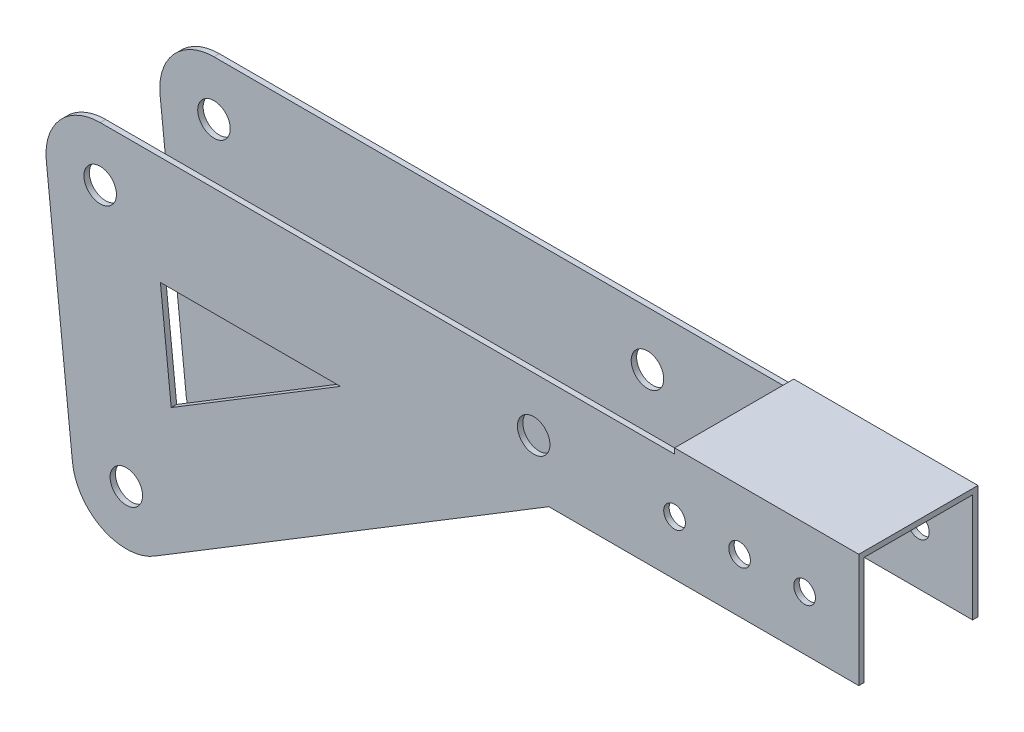
SolidWorks part; units mm, degrees
ref_plane "前视" through (0, 0, 0) normal (0, 0, 1) x (1, 0, 0)
ref_plane "上视" through (0, 0, 0) normal (0, 1, 0) x (1, 0, 0)
ref_plane "右视" through (0, 0, 0) normal (1, 0, 0) x (0, 0, -1)
sketch "草图1" plane through (0, 0, 0) normal (0, 0, 1) x (1, 0, 0)
  line L0 (-22.7233, 3.4621) -> (73.9869, 3.4621) construction
  line L1 (-6.5935, 20.8571) -> (-6.5935, -9.1197) construction
  line L2 (-6.5935, 8.4621) -> (63.4065, 8.4621)
  line L3 (-1.0384, -1.5379) -> (15.5717, -1.5379)
  line L4 (-11.5659, 2.9376) -> (-9.1534, -19.9355)
  line L5 (-1.5818, -23.6824) -> (34.8083, -1.5379)
  line L6 (-0.0366, -11.0361) -> (15.5717, -1.5379)
  line L7 (-1.0384, -1.5379) -> (-0.0366, -11.0361)
  line L8 (63.4065, 8.4621) -> (63.4065, -1.5379)
  line L9 (58.4065, 27.4351) -> (58.4065, -14.6669) construction
  line L10 (52.4065, -14.6579) -> (52.4065, 27.4351) construction
  line L11 (46.4065, 27.4351) -> (46.4065, -14.6579) construction
  line L12 (34.8083, -1.5379) -> (63.4065, -1.5379)
  circle A0 centre (-6.5935, 3.4621) radius 1.5
  circle A1 centre (33.4065, 3.4621) radius 1.5
  circle A2 centre (-4.181, -19.4111) radius 1.5
  arc A3 (-6.5935, 8.4621) -> (-11.5659, 2.9376) centre (-6.5935, 3.4621) ccw
  arc A4 (-9.1534, -19.9355) -> (-1.5818, -23.6824) centre (-4.181, -19.4111) ccw
  circle A5 centre (33.4065, 3.4621) radius 5 construction
  circle A6 centre (58.4065, 3.4621) radius 1
  circle A7 centre (52.4065, 3.4621) radius 1
  circle A8 centre (46.4065, 3.4621) radius 1
  dimension "D1" = 3
  dimension "D2" = 3
  dimension "D3" = 3
  dimension "D7" = 10
  dimension "D8" = 10
  dimension "D9" = 10
  dimension "D14" = 2
  dimension "D15" = 2
  dimension "D16" = 2
  dimension "D4" = 23
  dimension "D5" = 40
  dimension "D6" = 44
  dimension "D10" = 70
  dimension "D11" = 5
  dimension "D12" = 11
  dimension "D13" = 17
extrude "凸台-拉伸1" add sketch "草图1" along normal blind 0.5
ref_plane "基准面1" through (0, 0, -10) normal (0, 0, 1) x (1, 0, 0)
sketch "草图2" plane through (0, 0, -10) normal (0, 0, 1) x (1, 0, 0)
  line L3 (-0.0366, -11.0361) -> (15.5717, -1.5379)
  line L4 (-1.0384, -1.5379) -> (-0.0366, -11.0361)
  line L5 (15.5717, -1.5379) -> (-1.0384, -1.5379)
  line L6 (-0.0366, -11.0361) -> (15.5717, -1.5379)
  line L7 (-1.0384, -1.5379) -> (-0.0366, -11.0361)
  line L8 (15.5717, -1.5379) -> (-1.0384, -1.5379)
  line L11 (-1.5818, -23.6824) -> (34.8083, -1.5379)
  line L12 (-11.5659, 2.9376) -> (-9.1534, -19.9355)
  line L13 (63.4065, 8.4621) -> (-6.5935, 8.4621)
  line L14 (63.4065, -1.5379) -> (63.4065, 8.4621)
  line L15 (34.8083, -1.5379) -> (63.4065, -1.5379)
  line L16 (-1.5818, -23.6824) -> (34.8083, -1.5379)
  line L17 (-11.5659, 2.9376) -> (-9.1534, -19.9355)
  line L18 (63.4065, 8.4621) -> (-6.5935, 8.4621)
  line L19 (63.4065, -1.5379) -> (63.4065, 8.4621)
  line L20 (34.8083, -1.5379) -> (63.4065, -1.5379)
  circle A1 centre (-4.181, -19.4111) radius 1.5
  circle A2 centre (-4.181, -19.4111) radius 1.5
  circle A3 centre (33.4065, 3.4621) radius 1.5
  circle A4 centre (33.4065, 3.4621) radius 1.5
  circle A5 centre (-6.5935, 3.4621) radius 1.5
  circle A6 centre (-6.5935, 3.4621) radius 1.5
  circle A7 centre (52.4065, 3.4621) radius 1
  circle A8 centre (52.4065, 3.4621) radius 1
  circle A9 centre (58.4065, 3.4621) radius 1
  circle A10 centre (58.4065, 3.4621) radius 1
  circle A11 centre (46.4065, 3.4621) radius 1
  circle A12 centre (46.4065, 3.4621) radius 1
  arc A14 (-9.1534, -19.9355) -> (-1.5818, -23.6824) centre (-4.181, -19.4111) ccw
  arc A15 (-6.5935, 8.4621) -> (-11.5659, 2.9376) centre (-6.5935, 3.4621) ccw
  arc A16 (-9.1534, -19.9355) -> (-1.5818, -23.6824) centre (-4.181, -19.4111) ccw
  arc A17 (-6.5935, 8.4621) -> (-11.5659, 2.9376) centre (-6.5935, 3.4621) ccw
  dimension "D1" = 0
  dimension "D2" = 0
  dimension "D3" = 0
  dimension "D4" = 0
  dimension "D5" = 0
  dimension "D6" = 0
  dimension "D7" = 0
  dimension "D8" = 0
extrude "凸台-拉伸2" add sketch "草图2" against normal blind 0.5 separate body
ref_plane "基准面2" through (0, 8.4621, 0) normal (0, 1, 0) x (1, 0, 0)
sketch "草图3" plane through (0, 8.4621, 0) normal (0, 1, 0) x (1, 0, 0)
  line L0 (63.4065, 10.5) -> (63.4065, -0.5)
  line L1 (63.4065, -0.5) -> (46.4065, -0.5)
  line L2 (46.4065, -0.5) -> (46.4065, 0) construction
  line L3 (46.4065, -0.5) -> (46.4065, 10.5)
  line L4 (46.4065, 10.5) -> (46.4065, 10) construction
  line L5 (63.4065, 10.5) -> (-6.5935, 10.5) construction
  line L6 (46.4065, 10.5) -> (63.4065, 10.5)
extrude "凸台-拉伸3" add sketch "草图3" along normal blind 0.5
